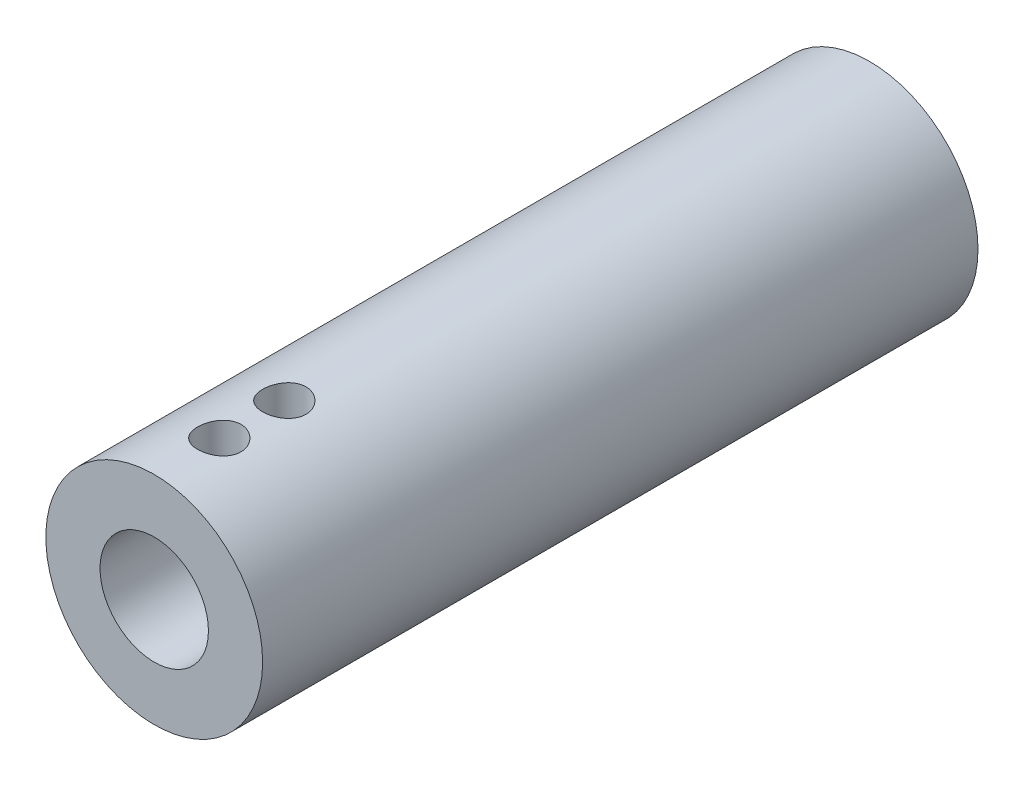
SolidWorks part; units mm, degrees
material "1060 Alloy"
ref_plane "Front Plane" through (0, 0, 0) normal (0, 0, 1) x (1, 0, 0)
ref_plane "Top Plane" through (0, 0, 0) normal (0, 1, 0) x (1, 0, 0)
ref_plane "Right Plane" through (0, 0, 0) normal (1, 0, 0) x (0, 0, -1)
sketch "Sketch1" plane through (0, 0, 0) normal (0, 0, 1) x (1, 0, 0)
  circle A1 centre (0, 0) radius 5
  dimension "D2" = 10
extrude "Boss-Extrude1" add sketch "Sketch1" along normal blind 33
sketch "Sketch2" plane through (0, 0, 33) normal (0, 0, 1) x (1, 0, 0)
  circle A0 centre (0, 0) radius 2.5
  dimension "D1" = 5
extrude "Cut-Extrude1" cut sketch "Sketch2" against normal blind 15
sketch "Sketch3" plane through (0, 0, 0) normal (0, 0, -1) x (-1, 0, 0)
  circle A0 centre (0, 0) radius 1.5
  dimension "D1" = 3
extrude "Cut-Extrude2" cut sketch "Sketch3" against normal blind 10
sketch "Sketch4" plane through (0, 0, 0) normal (0, 1, 0) x (1, 0, 0)
  line L0 (0, 33) -> (0, -33) construction
  line L2 (-5, -33) -> (5, -33) construction
  circle A0 centre (0, -30) radius 1
  circle A1 centre (0, -27) radius 1
  point P4 (0, 0)
  dimension "D1" = 2
  dimension "D2" = 3
  dimension "D3" = 3
extrude "Cut-Extrude3" cut sketch "Sketch4" along normal blind 10
